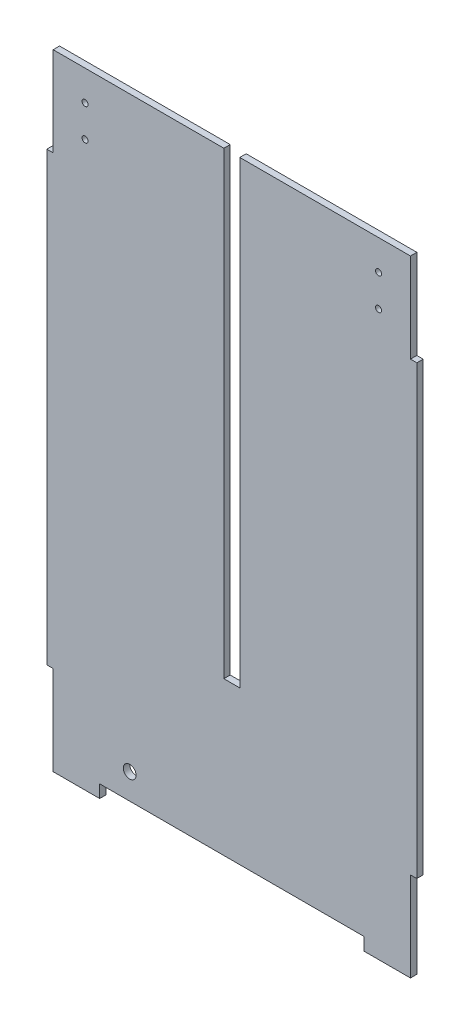
SolidWorks part; units mm, degrees
ref_plane "Front Plane" through (0, 0, 0) normal (0, 0, 1) x (1, 0, 0)
ref_plane "Top Plane" through (0, 0, 0) normal (0, 1, 0) x (1, 0, 0)
ref_plane "Right Plane" through (0, 0, 0) normal (1, 0, 0) x (0, 0, -1)
sketch "Sketch2" plane through (0, 0, 0) normal (0, 0, 1) x (1, 0, 0)
  line L0 (0, 152.4) -> (0, -152.4) construction
  line L1 (-88.9, 152.4) -> (88.9, 152.4)
  line L2 (-88.9, 152.4) -> (-88.9, -152.4)
  line L3 (-88.9, -152.4) -> (88.9, -152.4)
  line L4 (88.9, 152.4) -> (88.9, -152.4)
  line L5 (-88.9, 107.95) -> (-88.9, 63.5)
  line L6 (-88.9, 152.4) -> (-92.075, 152.4)
  line L7 (-88.9, 152.4) -> (-88.9, 107.95)
  line L8 (-88.9, 107.95) -> (-92.075, 107.95)
  line L9 (-92.075, 152.4) -> (-92.075, 107.95)
  line L10 (88.9, 152.4) -> (92.075, 152.4)
  line L11 (88.9, 152.4) -> (88.9, 107.95)
  line L12 (88.9, 107.95) -> (92.075, 107.95)
  line L13 (92.075, 152.4) -> (92.075, 107.95)
  line L14 (-65.7679, -152.4) -> (-92.075, -152.4)
  line L15 (-65.7679, -152.4) -> (-65.7679, -158.75)
  line L16 (-65.7679, -158.75) -> (-92.075, -158.75)
  line L17 (-92.075, -152.4) -> (-92.075, -158.75)
  line L18 (-88.9, 107.95) -> (-92.075, 107.95)
  line L19 (-92.075, 107.95) -> (-92.075, 63.5)
  line L20 (-88.9, 63.5) -> (-92.075, 63.5)
  line L21 (88.9, 107.95) -> (88.9, 63.5)
  line L22 (88.9, 107.95) -> (92.075, 107.95)
  line L23 (92.075, 107.95) -> (92.075, 63.5)
  line L24 (88.9, 63.5) -> (92.075, 63.5)
  line L25 (-88.9, 63.5) -> (-88.9, 19.05)
  line L26 (-88.9, 63.5) -> (-92.075, 63.5)
  line L27 (-92.075, 63.5) -> (-92.075, 19.05)
  line L28 (-88.9, 19.05) -> (-92.075, 19.05)
  line L29 (88.9, 63.5) -> (88.9, 19.05)
  line L30 (88.9, 63.5) -> (92.075, 63.5)
  line L31 (92.075, 63.5) -> (92.075, 19.05)
  line L32 (88.9, 19.05) -> (92.075, 19.05)
  line L33 (-88.9, 19.05) -> (-88.9, -25.4)
  line L34 (-88.9, 19.05) -> (-92.075, 19.05)
  line L35 (-92.075, 19.05) -> (-92.075, -25.4)
  line L36 (-88.9, -25.4) -> (-92.075, -25.4)
  line L37 (88.9, 19.05) -> (88.9, -25.4)
  line L38 (88.9, 19.05) -> (92.075, 19.05)
  line L39 (92.075, 19.05) -> (92.075, -25.4)
  line L40 (88.9, -25.4) -> (92.075, -25.4)
  line L41 (-88.9, -25.4) -> (-88.9, -69.85)
  line L42 (-88.9, -25.4) -> (-92.075, -25.4)
  line L43 (-92.075, -25.4) -> (-92.075, -69.85)
  line L44 (-88.9, -69.85) -> (-92.075, -69.85)
  line L45 (88.9, -25.4) -> (88.9, -69.85)
  line L46 (88.9, -25.4) -> (92.075, -25.4)
  line L47 (92.075, -25.4) -> (92.075, -69.85)
  line L48 (88.9, -69.85) -> (92.075, -69.85)
  line L49 (-88.9, -69.85) -> (-88.9, -114.3)
  line L50 (-88.9, -69.85) -> (-92.075, -69.85)
  line L51 (-92.075, -69.85) -> (-92.075, -114.3)
  line L52 (-88.9, -114.3) -> (-92.075, -114.3)
  line L53 (88.9, -69.85) -> (88.9, -114.3)
  line L54 (88.9, -69.85) -> (92.075, -69.85)
  line L55 (92.075, -69.85) -> (92.075, -114.3)
  line L56 (88.9, -114.3) -> (92.075, -114.3)
  line L57 (-88.9, -114.3) -> (-88.9, -158.75)
  line L58 (-88.9, -114.3) -> (-92.075, -114.3)
  line L59 (-92.075, -114.3) -> (-92.075, -158.75)
  line L60 (-88.9, -158.75) -> (-92.075, -158.75)
  line L61 (88.9, -114.3) -> (88.9, -158.75)
  line L62 (88.9, -114.3) -> (92.075, -114.3)
  line L63 (92.075, -114.3) -> (92.075, -158.75)
  line L64 (88.9, -158.75) -> (92.075, -158.75)
  line L65 (-39.4607, -152.4) -> (-39.4607, -158.75)
  line L66 (-39.4607, -152.4) -> (-65.7679, -152.4)
  line L67 (-65.7679, -152.4) -> (-65.7679, -158.75)
  line L68 (-39.4607, -158.75) -> (-65.7679, -158.75)
  line L69 (-13.1536, -152.4) -> (-13.1536, -158.75)
  line L70 (-13.1536, -152.4) -> (-39.4607, -152.4)
  line L71 (-39.4607, -152.4) -> (-39.4607, -158.75)
  line L72 (-13.1536, -158.75) -> (-39.4607, -158.75)
  line L73 (13.1536, -152.4) -> (13.1536, -158.75)
  line L74 (13.1536, -152.4) -> (-13.1536, -152.4)
  line L75 (-13.1536, -152.4) -> (-13.1536, -158.75)
  line L76 (13.1536, -158.75) -> (-13.1536, -158.75)
  line L77 (39.4607, -152.4) -> (39.4607, -158.75)
  line L78 (39.4607, -152.4) -> (13.1536, -152.4)
  line L79 (13.1536, -152.4) -> (13.1536, -158.75)
  line L80 (39.4607, -158.75) -> (13.1536, -158.75)
  line L81 (65.7679, -152.4) -> (65.7679, -158.75)
  line L82 (65.7679, -152.4) -> (39.4607, -152.4)
  line L83 (39.4607, -152.4) -> (39.4607, -158.75)
  line L84 (65.7679, -158.75) -> (39.4607, -158.75)
  line L85 (92.075, -152.4) -> (92.075, -158.75)
  line L86 (92.075, -152.4) -> (65.7679, -152.4)
  line L87 (65.7679, -152.4) -> (65.7679, -158.75)
  line L88 (92.075, -158.75) -> (65.7679, -158.75)
  point P6 (0, 0)
  dimension "D1" = 177.8
  dimension "D2" = 184.15
  dimension "D3" = 304.8
  dimension "D4" = 311.15
  dimension "D6" = 44.45
  dimension "D8" = 26.3071
  dimension "D5" = 7
  dimension "D7" = 7
extrude "Boss-Extrude1" add sketch "Sketch2" along normal blind 3.175 contours L0 L1 L2 L3 | L1 L0 L3 L4 | L20 L2 L8 L19 | L36 L2 L28 L35 | L52 L2 L44 L51 | L3 L57 L16 L15 | L72 L69 L3 L65 | L80 L77 L3 L73 | L4 L56 L55 L48 | L4 L40 L39 L32 | L4 L24 L23 L12 | L88 L61 L3 L81
sketch "Sketch3" plane through (0, 0, 3.175) normal (0, 0, 1) x (1, 0, 0)
  line L0 (-88.9, 152.4) -> (88.9, 152.4) construction
  line L1 (-3.9688, 152.4) -> (3.9687, 152.4)
  line L2 (-3.9688, 152.4) -> (-3.9687, -76.2)
  line L3 (-3.9687, -76.2) -> (3.9688, -76.2)
  line L4 (3.9687, 152.4) -> (3.9688, -76.2)
  line L5 (0, -76.2) -> (0, 0) construction
  dimension "D1" = 7.9375
  dimension "D2" = 228.6
extrude "Cut-Extrude1" cut sketch "Sketch3" against normal through all
sketch "Sketch4" plane through (0, 0, 3.175) normal (0, 0, 1) x (1, 0, 0)
  line L0 (-65.7679, -152.4) -> (-39.4607, -152.4) construction
  line L1 (-88.9, -114.3) -> (-88.9, -158.75) construction
  circle A0 centre (-50.8, -139.7) radius 3.175
  dimension "D1" = 6.35
  dimension "D2" = 12.7
  dimension "D3" = 38.1
extrude "Cut-Extrude2" cut sketch "Sketch4" against normal through all
sketch "Sketch5" plane through (0, 0, 3.175) normal (0, 0, 1) x (1, 0, 0)
  line L0 (0, -152.4) -> (0, 152.4) construction
  line L1 (-13.1536, -152.4) -> (13.1536, -152.4) construction
  line L2 (3.9687, 152.4) -> (88.9, 152.4) construction
  line L3 (-88.9, 152.4) -> (-3.9688, 152.4) construction
  line L5 (-92.075, 107.95) -> (-92.075, 63.5) construction
  circle A0 centre (-73.025, 137.4) radius 1.5
  circle A1 centre (-73.025, 121.65) radius 1.5
  circle A2 centre (73.025, 121.65) radius 1.5
  circle A3 centre (73.025, 137.4) radius 1.5
  dimension "D1" = 15.75
  dimension "D2" = 15
  dimension "D4" = 3
  dimension "D5" = 3
  dimension "D3" = 19.05
extrude "Cut-Extrude3" cut sketch "Sketch5" against normal up to surface (3.175 mm away) up to face at (-47.625, -139.7, 0)
sketch "Sketch6" plane through (0, 0, 3.175) normal (0, 0, 1) x (1, 0, 0)
  line L1 (-92.075, 63.5) -> (-88.9, 63.5)
  line L2 (-92.075, 63.5) -> (-92.075, 19.05)
  line L3 (-92.075, 19.05) -> (-88.9, 19.05)
  line L4 (-88.9, 63.5) -> (-88.9, 19.05)
  line L5 (-92.075, -25.4) -> (-88.9, -25.4)
  line L6 (-92.075, -25.4) -> (-92.075, -69.85)
  line L7 (-92.075, -69.85) -> (-88.9, -69.85)
  line L8 (-88.9, -25.4) -> (-88.9, -69.85)
  line L9 (92.075, 63.5) -> (88.9, 63.5)
  line L10 (92.075, 63.5) -> (92.075, 19.05)
  line L11 (92.075, 19.05) -> (88.9, 19.05)
  line L12 (88.9, 63.5) -> (88.9, 19.05)
  line L13 (88.9, -25.4) -> (92.075, -25.4)
  line L14 (88.9, -25.4) -> (88.9, -69.85)
  line L15 (88.9, -69.85) -> (92.075, -69.85)
  line L16 (92.075, -25.4) -> (92.075, -69.85)
extrude "Boss-Extrude2" add sketch "Sketch6" against normal up to surface (3.175 mm away) up to face at (74.525, 137.4, 0)
sketch "Sketch7" plane through (0, 0, 3.175) normal (0, 0, 1) x (1, 0, 0)
  line L1 (-39.4607, -152.4) -> (-13.1536, -152.4)
  line L2 (-39.4607, -152.4) -> (-39.4607, -158.75)
  line L3 (-39.4607, -158.75) -> (-13.1536, -158.75)
  line L4 (-13.1536, -152.4) -> (-13.1536, -158.75)
  line L5 (13.1536, -152.4) -> (39.4607, -152.4)
  line L6 (13.1536, -152.4) -> (13.1536, -158.75)
  line L7 (13.1536, -158.75) -> (39.4607, -158.75)
  line L8 (39.4607, -152.4) -> (39.4607, -158.75)
extrude "Cut-Extrude4" cut sketch "Sketch7" against normal up to surface (3.175 mm away) up to face at (0, -62.5929, 0)
equation "\"Height\"= 12in"
equation "\"Depth\"= 7in"
equation "\"WallThickness\"= 0.125in"
equation "\"FloorThickness\"= 0.25in"
equation "\"D1@Sketch2\"=\"Depth\""
equation "\"D2@Sketch2\"=\"D1@Sketch2\"+2*\"WallThickness\""
equation "\"D3@Sketch2\"=\"Height\""
equation "\"D4@Sketch2\"=\"D3@Sketch2\"+\"FloorThickness\""
equation "\"D6@Sketch2\"=\"D4@Sketch2\"/\"D5@Sketch2\""
equation "\"D8@Sketch2\"=\"D2@Sketch2\"/\"D7@Sketch2\""
equation "\"D1@Boss-Extrude1\"=\"WallThickness\""
equation "\"Width\" = 30in"
